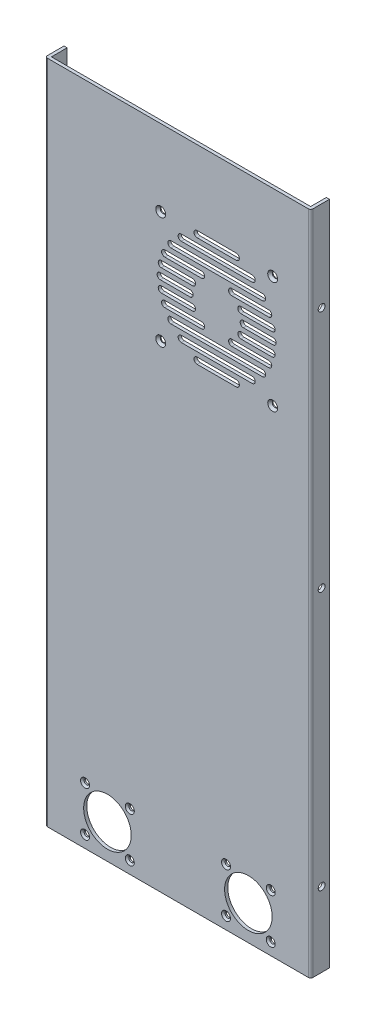
SolidWorks part; units mm, degrees
ref_plane "Front Plane" through (0, 0, 0) normal (0, 0, 1) x (1, 0, 0)
ref_plane "Top Plane" through (0, 0, 0) normal (0, 1, 0) x (1, 0, 0)
ref_plane "Right Plane" through (0, 0, 0) normal (1, 0, 0) x (0, 0, -1)
sketch "Sketch1" plane through (0, 0, 0) normal (0, 1, 0) x (1, 0, 0)
  line L0 (-84.75, 12) -> (-84.75, 1.5)
  line L1 (-83.25, 0) -> (83.25, 0)
  line L2 (84.75, 1.5) -> (84.75, 12)
  arc A0 (83.25, 0) -> (84.75, 1.5) centre (83.25, 1.5) ccw
  arc A1 (-84.75, 1.5) -> (-83.25, 0) centre (-83.25, 1.5) ccw
  point P7 (84.75, 0)
  point P10 (-84.75, 0)
  dimension "D3" = 1.5
  dimension "D1" = 12
  dimension "D2" = 169.5
extrude "Extrude-Thin1" add sketch "Sketch1" along normal blind 425 thin
sketch "Sketch2" plane through (0, 0, -2) normal (0, 0, -1) x (-1, 0, 0)
  line L0 (-60.5, 376.25) -> (11, 304.75) construction
  line L1 (-60.75, 340.5) -> (-41.75, 340.5) construction
  line L2 (-60.75, 342.5) -> (-41.75, 342.5)
  line L3 (-60.75, 338.5) -> (-41.75, 338.5)
  line L4 (-7.75, 340.5) -> (11.25, 340.5) construction
  line L5 (-7.75, 342.5) -> (11.25, 342.5)
  line L6 (-7.75, 338.5) -> (11.25, 338.5)
  line L7 (-60.0629, 347.5) -> (-40.2419, 347.5) construction
  line L8 (-60.0629, 349.5) -> (-40.2419, 349.5)
  line L9 (-60.0629, 345.5) -> (-40.2419, 345.5)
  line L10 (-57.9162, 354.5) -> (-34.3937, 354.5) construction
  line L11 (-57.9162, 356.5) -> (-34.3937, 356.5)
  line L12 (-57.9162, 352.5) -> (-34.3937, 352.5)
  line L13 (-9.2581, 347.5) -> (10.5629, 347.5) construction
  line L14 (-9.2581, 349.5) -> (10.5629, 349.5)
  line L15 (-9.2581, 345.5) -> (10.5629, 345.5)
  line L16 (-15.1063, 354.5) -> (8.4162, 354.5) construction
  line L17 (-15.1063, 356.5) -> (8.4162, 356.5)
  line L18 (-15.1063, 352.5) -> (8.4162, 352.5)
  line L19 (-9.2581, 333.5) -> (10.5629, 333.5) construction
  line L20 (-9.2581, 335.5) -> (10.5629, 335.5)
  line L21 (-9.2581, 331.5) -> (10.5629, 331.5)
  line L22 (-15.1063, 326.5) -> (8.4162, 326.5) construction
  line L23 (-15.1063, 328.5) -> (8.4162, 328.5)
  line L24 (-15.1063, 324.5) -> (8.4162, 324.5)
  line L25 (-60.0629, 333.5) -> (-40.2419, 333.5) construction
  line L26 (-60.0629, 335.5) -> (-40.2419, 335.5)
  line L27 (-60.0629, 331.5) -> (-40.2419, 331.5)
  line L28 (-57.9162, 326.5) -> (-34.3937, 326.5) construction
  line L29 (-57.9162, 328.5) -> (-34.3937, 328.5)
  line L30 (-57.9162, 324.5) -> (-34.3937, 324.5)
  line L31 (-9.2581, 326.5) -> (-9.2581, 333.5) construction
  line L32 (-9.2581, 333.5) -> (-9.2581, 340.5) construction
  line L33 (-9.2581, 340.5) -> (-9.2581, 347.5) construction
  line L34 (-9.2581, 347.5) -> (-9.2581, 354.5) construction
  line L35 (-53.9904, 361.5) -> (4.4904, 361.5) construction
  line L36 (-53.9904, 363.5) -> (4.4904, 363.5)
  line L37 (-53.9904, 359.5) -> (4.4904, 359.5)
  line L38 (-47.3774, 368.5) -> (-2.1226, 368.5) construction
  line L39 (-47.3774, 370.5) -> (-2.1226, 370.5)
  line L40 (-47.3774, 366.5) -> (-2.1226, 366.5)
  line L41 (-37.25, 375.5) -> (-12.25, 375.5) construction
  line L42 (-37.25, 377.5) -> (-12.25, 377.5)
  line L43 (-37.25, 373.5) -> (-12.25, 373.5)
  line L44 (-53.9904, 319.5) -> (4.4904, 319.5) construction
  line L45 (-53.9904, 321.5) -> (4.4904, 321.5)
  line L46 (-53.9904, 317.5) -> (4.4904, 317.5)
  line L47 (-47.3774, 312.5) -> (-2.1226, 312.5) construction
  line L48 (-47.3774, 314.5) -> (-2.1226, 314.5)
  line L49 (-47.3774, 310.5) -> (-2.1226, 310.5)
  line L50 (-37.25, 305.5) -> (-12.25, 305.5) construction
  line L51 (-37.25, 307.5) -> (-12.25, 307.5)
  line L52 (-37.25, 303.5) -> (-12.25, 303.5)
  line L53 (-6.5471, 361.5) -> (-6.5471, 354.5) construction
  line L54 (-0.9392, 366.5782) -> (-1.2008, 366.5782) construction
  line L55 (-16.7711, 361.5) -> (-16.7711, 368.5) construction
  line L56 (-20.173, 368.5) -> (-20.173, 375.5) construction
  line L57 (-12.9767, 326.5) -> (-12.9767, 319.5) construction
  line L58 (-12.25, 319.5) -> (-12.25, 312.5) construction
  line L59 (-16.0327, 312.5) -> (-16.0327, 305.5) construction
  line L60 (-24.75, 340.5) -> (-24.75, 375.5) construction
  line L61 (82.75, 0) -> (-82.75, 0) construction
  line L62 (-59.2875, 36.2875) -> (-30.7125, 7.7125) construction
  line L63 (30.7125, 7.7125) -> (59.2875, 36.2875) construction
  line L64 (-65, 0) -> (-65, 69.7756) construction
  circle A0 centre (-60.5, 376.25) radius 1
  circle A1 centre (11, 376.25) radius 1
  circle A2 centre (-60.5, 304.75) radius 1
  circle A3 centre (11, 304.75) radius 1
  circle A4 centre (-24.75, 340.5) radius 15 construction
  circle A5 centre (-24.75, 340.5) radius 38 construction
  arc A6 (-60.75, 342.5) -> (-60.75, 338.5) centre (-60.75, 340.5) ccw
  arc A7 (-41.75, 338.5) -> (-41.75, 342.5) centre (-41.75, 340.5) ccw
  arc A8 (-7.75, 342.5) -> (-7.75, 338.5) centre (-7.75, 340.5) ccw
  arc A9 (11.25, 338.5) -> (11.25, 342.5) centre (11.25, 340.5) ccw
  arc A10 (-60.0629, 349.5) -> (-60.0629, 345.5) centre (-60.0629, 347.5) ccw
  arc A11 (-40.2419, 345.5) -> (-40.2419, 349.5) centre (-40.2419, 347.5) ccw
  arc A12 (-57.9162, 356.5) -> (-57.9162, 352.5) centre (-57.9162, 354.5) ccw
  arc A13 (-34.3937, 352.5) -> (-34.3937, 356.5) centre (-34.3937, 354.5) ccw
  arc A14 (-9.2581, 349.5) -> (-9.2581, 345.5) centre (-9.2581, 347.5) ccw
  arc A15 (10.5629, 345.5) -> (10.5629, 349.5) centre (10.5629, 347.5) ccw
  arc A16 (-15.1063, 356.5) -> (-15.1063, 352.5) centre (-15.1063, 354.5) ccw
  arc A17 (8.4162, 352.5) -> (8.4162, 356.5) centre (8.4162, 354.5) ccw
  arc A18 (-9.2581, 335.5) -> (-9.2581, 331.5) centre (-9.2581, 333.5) ccw
  arc A19 (10.5629, 331.5) -> (10.5629, 335.5) centre (10.5629, 333.5) ccw
  arc A20 (-15.1063, 328.5) -> (-15.1063, 324.5) centre (-15.1063, 326.5) ccw
  arc A21 (8.4162, 324.5) -> (8.4162, 328.5) centre (8.4162, 326.5) ccw
  arc A22 (-60.0629, 335.5) -> (-60.0629, 331.5) centre (-60.0629, 333.5) ccw
  arc A23 (-40.2419, 331.5) -> (-40.2419, 335.5) centre (-40.2419, 333.5) ccw
  arc A24 (-57.9162, 328.5) -> (-57.9162, 324.5) centre (-57.9162, 326.5) ccw
  arc A25 (-34.3937, 324.5) -> (-34.3937, 328.5) centre (-34.3937, 326.5) ccw
  arc A26 (-53.9904, 363.5) -> (-53.9904, 359.5) centre (-53.9904, 361.5) ccw
  arc A27 (4.4904, 359.5) -> (4.4904, 363.5) centre (4.4904, 361.5) ccw
  arc A28 (-47.3774, 370.5) -> (-47.3774, 366.5) centre (-47.3774, 368.5) ccw
  arc A29 (-2.1226, 366.5) -> (-2.1226, 370.5) centre (-2.1226, 368.5) ccw
  arc A30 (-37.25, 377.5) -> (-37.25, 373.5) centre (-37.25, 375.5) ccw
  arc A31 (-12.25, 373.5) -> (-12.25, 377.5) centre (-12.25, 375.5) ccw
  arc A32 (-53.9904, 321.5) -> (-53.9904, 317.5) centre (-53.9904, 319.5) ccw
  arc A33 (4.4904, 317.5) -> (4.4904, 321.5) centre (4.4904, 319.5) ccw
  arc A34 (-47.3774, 314.5) -> (-47.3774, 310.5) centre (-47.3774, 312.5) ccw
  arc A35 (-2.1226, 310.5) -> (-2.1226, 314.5) centre (-2.1226, 312.5) ccw
  arc A36 (-37.25, 307.5) -> (-37.25, 303.5) centre (-37.25, 305.5) ccw
  arc A37 (-12.25, 303.5) -> (-12.25, 307.5) centre (-12.25, 305.5) ccw
  circle A38 centre (45, 22) radius 15.187
  circle A39 centre (-45, 22) radius 15.187
  circle A40 centre (-59.2875, 7.7125) radius 1
  circle A41 centre (-30.7125, 7.7125) radius 1
  circle A42 centre (-30.7125, 36.2875) radius 1
  circle A43 centre (-59.2875, 36.2875) radius 1
  circle A44 centre (30.7125, 36.2875) radius 1
  circle A45 centre (59.2875, 36.2875) radius 1
  circle A46 centre (59.2875, 7.7125) radius 1
  circle A47 centre (30.7125, 7.7125) radius 1
  point P17 (-51.25, 340.5)
  point P24 (1.75, 340.5)
  point P31 (-50.1524, 347.5)
  point P36 (-46.1549, 354.5)
  point P43 (0.6524, 347.5)
  point P50 (-3.3451, 354.5)
  point P57 (0.6524, 333.5)
  point P64 (-3.3451, 326.5)
  point P71 (-50.1524, 333.5)
  point P78 (-46.1549, 326.5)
  point P92 (-24.75, 361.5)
  point P97 (-24.75, 368.5)
  point P104 (-24.75, 375.5)
  point P111 (-24.75, 319.5)
  point P118 (-24.75, 312.5)
  point P125 (-24.75, 305.5)
  dimension "D1" = 2
  dimension "D2" = 30
  dimension "D3" = 76
  dimension "D4" = 2
  dimension "D10" = 30.374
  dimension "D13" = 30.374
  dimension "D16" = 2
  dimension "D17" = 2
  dimension "D5" = 7
  dimension "D6" = 25
  dimension "D7" = 22
  dimension "D8" = 45
  dimension "D9" = 45
  dimension "D11" = 28.575
  dimension "D12" = 28.575
  dimension "D14" = 28.575
  dimension "D15" = 28.575
  dimension "D18" = 65
extrude "Cut-Extrude1" cut sketch "Sketch2" against normal blind 10
sketch "Sketch3" plane through (-84.75, 0, 0) normal (-1, 0, 0) x (0, 0, 1)
  line L0 (-12, 425) -> (-12, 0) construction
  line L1 (-12, 212.5) -> (-7, 212.5) construction
  circle A0 centre (-7, 367.5) radius 2.195
  circle A1 centre (-7, 212.5) radius 2.195
  circle A2 centre (-7, 47.5) radius 2.195
  dimension "D4" = 4.39
  dimension "D1" = 5
  dimension "D2" = 155
  dimension "D3" = 165
extrude "Cut-Extrude2" cut sketch "Sketch3" against normal through all
hole_wizard "CSK for #4 Flat Head Machine Screw (100)1" positions "Sketch7" profile "Sketch6" countersink size "#4" standard "Ansi Inch"
sketch "Sketch7" plane through (0, 0, 0) normal (0, 0, 1) x (1, 0, 0)
  point P0 (-59.2875, 36.2875)
  point P1 (-59.2875, 7.7125)
  point P4 (-30.7125, 7.7125)
  point P7 (-30.7125, 36.2875)
  point P10 (30.7125, 36.2875)
  point P13 (59.2875, 36.2875)
  point P16 (59.2875, 7.7125)
  point P19 (30.7125, 7.7125)
sketch "Sketch6" plane through (-59.2875, 36.2875, 0) normal (1, 0, 0) x (0, -1, 0)
  line L0 (0, 0) -> (0, 10.9806)
  line L1 (0, 10.9806) -> (1.6319, 10)
  line L2 (1.6319, 10) -> (1.6319, 1.0284)
  line L3 (1.6319, 1.0284) -> (2.8575, 0)
  line L5 (2.8575, 0) -> (0, 0)
  line L6 (-1.6319, 1.0284) -> (-2.8575, 0) construction
  line L10 (0, 10.9806) -> (-1.6319, 10) construction
  line L11 (0, -6.35) -> (0, 107.95) construction
  dimension "Hole Dia." = 3.2639
  dimension "Hole Depth" = 10
  dimension "Near C'Sink Dia." = 5.715
  dimension "Near C'Sink Angle" = 100
  dimension "Drill Angle" = 118
hole_wizard "CSK for M3 Flat Head Machine Screw1" positions "Sketch9" profile "Sketch8" countersink size "M3" standard "Ansi Metric"
sketch "Sketch9" plane through (0, 0, 0) normal (0, 0, 1) x (1, 0, 0)
  point P0 (-11, 376.25)
  point P1 (60.5, 376.25)
  point P4 (60.5, 304.75)
  point P7 (-11, 304.75)
sketch "Sketch8" plane through (-11, 376.25, 0) normal (1, 0, 0) x (0, -1, 0)
  line L0 (0, 0) -> (0, 11.0215)
  line L1 (0, 11.0215) -> (1.7, 10)
  line L2 (1.7, 10) -> (1.7, 1.45)
  line L3 (1.7, 1.45) -> (3.15, 0)
  line L5 (3.15, 0) -> (0, 0)
  line L6 (-1.7, 1.45) -> (-3.15, 0) construction
  line L10 (0, 11.0215) -> (-1.7, 10) construction
  line L11 (0, -6.35) -> (0, 107.95) construction
  dimension "Hole Dia." = 3.4
  dimension "Hole Depth" = 10
  dimension "Near C'Sink Dia." = 6.3
  dimension "Near C'Sink Angle" = 90
  dimension "Drill Angle" = 118
